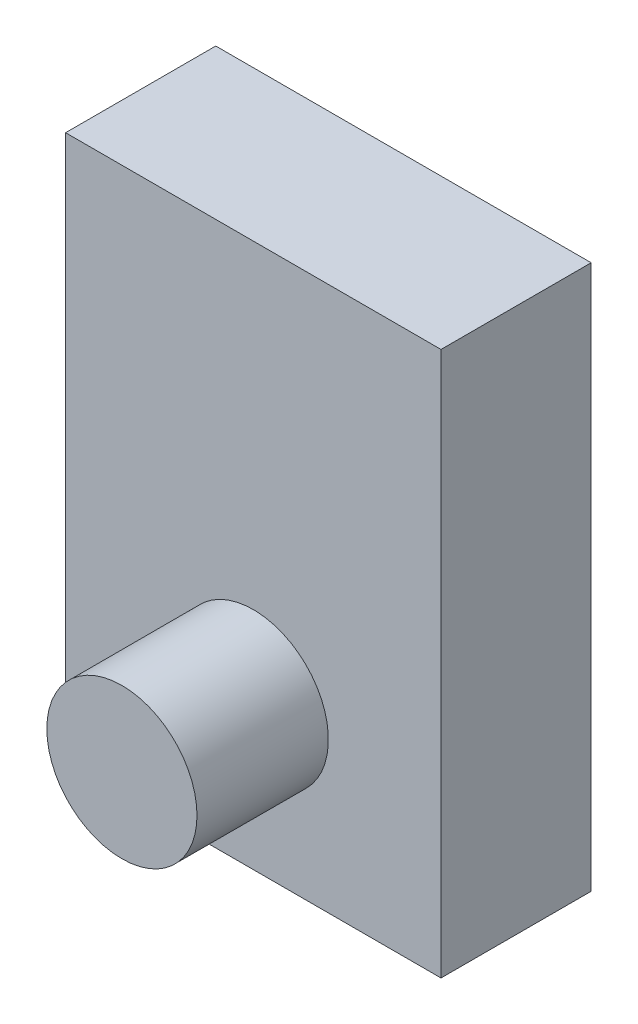
SolidWorks part; units mm, degrees
ref_plane "Front Plane" through (0, 0, 0) normal (0, 0, 1) x (1, 0, 0)
ref_plane "Top Plane" through (0, 0, 0) normal (0, 1, 0) x (1, 0, 0)
ref_plane "Right Plane" through (0, 0, 0) normal (1, 0, 0) x (0, 0, -1)
sketch "SK_P01_Hanger" plane through (0, 0, 0) normal (0, 1, 0) x (1, 0, 0)
  line L0 (-10, -1.5) -> (10, -1.5)
  line L1 (10, -1.5) -> (10, 6.5)
  line L2 (10, 6.5) -> (-10, 6.5)
  line L3 (-10, 6.5) -> (-10, -1.5)
extrude "P01_Hanger" add sketch "SK_P01_Hanger" along normal blind 29
sketch "SK_P02_Pivotpin8mm" plane through (0, 0, 0) normal (0, 0, 1) x (1, 0, 0)
  circle A0 centre (0, 8) radius 4
extrude "P02_Pivotpin8mm" add sketch "SK_P02_Pivotpin8mm" along normal blind 17 from offset 8.5
